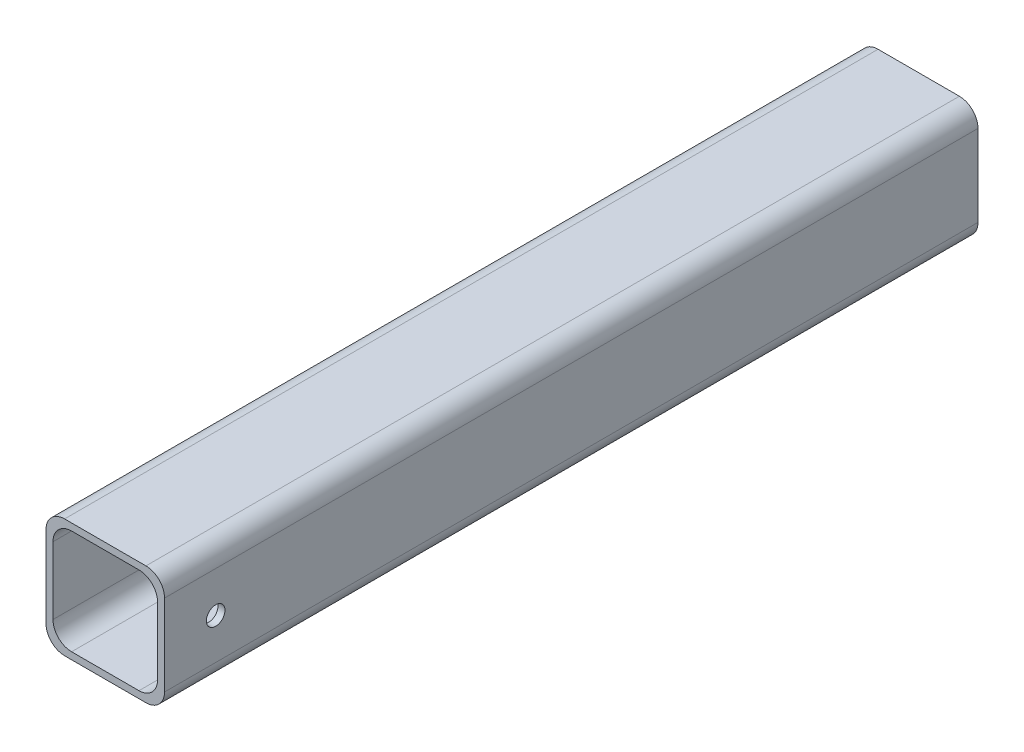
SolidWorks part; units mm, degrees
ref_plane "Front Plane" through (0, 0, 0) normal (0, 0, 1) x (1, 0, 0)
ref_plane "Top Plane" through (0, 0, 0) normal (0, 1, 0) x (1, 0, 0)
ref_plane "Right Plane" through (0, 0, 0) normal (1, 0, 0) x (0, 0, -1)
sketch "Sketch4" plane through (0, 0, 0) normal (0, 0, 1) x (1, 0, 0)
  line L0 (1.5, 1.5) -> (1.5, 24)
  line L1 (0, 0) -> (25.5, 0)
  line L2 (0, 0) -> (0, 25.5)
  line L3 (0, 25.5) -> (25.5, 25.5)
  line L4 (25.5, 0) -> (25.5, 25.5)
  line L5 (1.5, 24) -> (24, 24)
  line L6 (24, 1.5) -> (24, 24)
  line L7 (1.5, 1.5) -> (24, 1.5)
  dimension "D1" = 1.5
extrude "Boss-Extrude1" add sketch "Sketch4" along normal blind 175
sketch "Sketch5" plane through (25.5, 0, 0) normal (1, 0, 0) x (0, 0, -1)
  line L0 (-175, 12.75) -> (-101.152, 12.75) construction
  line L1 (-175, 0) -> (-175, 25.5) construction
  circle A0 centre (-164, 12.75) radius 2
  dimension "D1" = 11
  dimension "D2" = 4
extrude "Cut-Extrude1" cut sketch "Sketch5" against normal up to surface (1.5 mm away) up to face at (24, 12.75, 87.5)
fillet "Fillet1" radius 4 8 edges at (0, 25.5, 87.5) (0, 0, 87.5) (25.5, 0, 87.5) (25.5, 25.5, 87.5) (24, 24, 87.5) (1.5, 24, 87.5) (1.5, 1.5, 87.5) (24, 1.5, 87.5)
